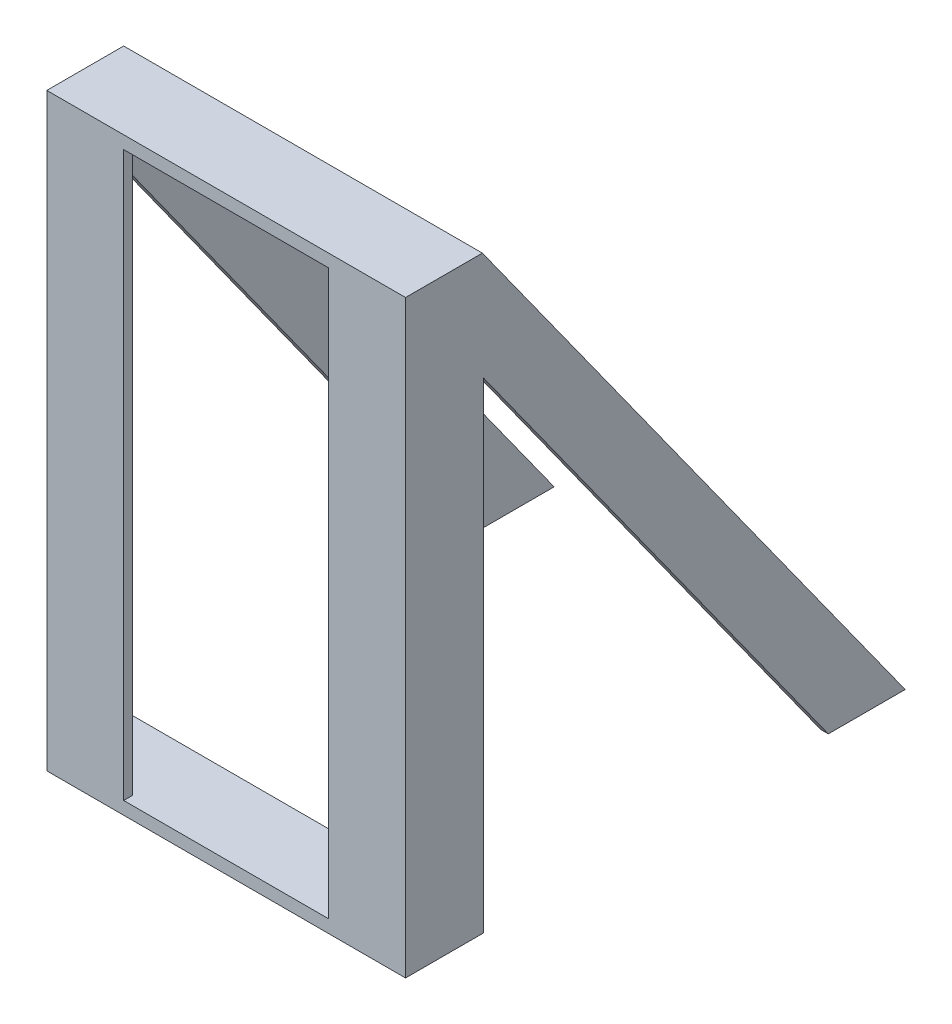
SolidWorks part; units mm, degrees
ref_plane "Front Plane" through (0, 0, 0) normal (0, 0, 1) x (1, 0, 0)
ref_plane "Top Plane" through (0, 0, 0) normal (0, 1, 0) x (1, 0, 0)
ref_plane "Right Plane" through (0, 0, 0) normal (1, 0, 0) x (0, 0, -1)
sketch "Sketch1" plane through (0, 0, 0) normal (0, 1, 0) x (1, 0, 0)
  line L0 (0, 0) -> (0, 30)
  line L1 (0, 0) -> (30, 0)
  line L2 (0, 30) -> (3.4, 30)
  line L3 (30, 0) -> (30, 3.4)
  line L6 (3.4, 30) -> (3.4, 3.4)
  line L7 (3.4, 3.4) -> (30, 3.4)
extrude "Boss-Extrude1" add sketch "Sketch1" along normal blind 225
sketch "Sketch2" plane through (0, 0, 0) normal (0, -1, 0) x (-1, 0, 0)
  line L0 (0, 0) -> (-140, 0)
  line L2 (0, 0) -> (-140, 0)
  line L3 (0, 0) -> (0, 30.4234)
  line L4 (0, 30.4234) -> (-140, 30.4234)
  line L5 (-140, 0) -> (-140, 30.4234)
  line M3 (0, 30) -> (-3.4, 30)
  line M4 (-3.4, 30) -> (-3.4, 3.4)
  line M5 (-3.4, 3.4) -> (-30, 3.4)
  line M6 (-30, 3.4) -> (-30, 0)
extrude "Boss-Extrude2" add sketch "Sketch2" against normal blind 5 contours L5 L0 L3 L4 M6 M5 M4 M3
sketch "Sketch3" plane through (0, 5, 0) normal (0, 1, 0) x (1, 0, 0)
  line L0 (140, 30.4234) -> (136.6, 30.4234)
  line L1 (0, 30.4234) -> (140, 30.4234) construction
  line L2 (140, 0) -> (110, 0)
  line L3 (30, 0) -> (140, 0) construction
  line L4 (110, 0) -> (110, 3.4)
  line L5 (136.6, 30.4234) -> (136.6, 3.4)
  line L6 (136.6, 3.4) -> (110, 3.4)
  line L15 (140, 0) -> (140, 30.4234)
  line L16 (140, 30.4234) -> (0, 30.4234)
  line L17 (0, 30.4234) -> (0, 30)
  line L18 (0, 30) -> (3.4, 30)
  line L19 (3.4, 30) -> (3.4, 3.4)
  line L20 (3.4, 3.4) -> (30, 3.4)
  line L21 (30, 3.4) -> (30, 0)
  line L22 (30, 0) -> (140, 0)
  line L24 (140, 30.4234) -> (0, 30.4234)
  line L25 (0, 30.4234) -> (0, 30)
  line L26 (0, 30) -> (3.4, 30)
  line L27 (3.4, 30) -> (3.4, 3.4)
  line L28 (3.4, 3.4) -> (30, 3.4)
  line L29 (30, 3.4) -> (30, 0)
  line L30 (30, 0) -> (140, 0)
  line M12 (140, 0) -> (140, 30.4234)
  line M13 (140, 30.4234) -> (0, 30.4234)
  line M19 (30, 0) -> (140, 0)
  dimension "D1" = 0
extrude "Boss-Extrude3" add sketch "Sketch3" along normal blind 220 contours L5 L6 L4 M19 M12 M13
sketch "Sketch4" plane through (0, 225, 0) normal (0, 1, 0) x (1, 0, 0)
  line L1 (0, 30) -> (140, 30)
  line L2 (0, 30) -> (0, 0)
  line L3 (0, 0) -> (140, 0)
  line L4 (140, 30) -> (140, 0)
extrude "Boss-Extrude4" add sketch "Sketch4" along normal blind 5
sketch "Sketch5" plane through (140, 0, 0) normal (1, 0, 0) x (0, 0, -1)
  line L0 (0, 0) -> (195, 0)
  line L1 (30, 230) -> (195, 0)
  line L2 (0, 0) -> (0, 30)
  line L3 (0, 30) -> (143.4783, 30)
  line L4 (195, 0) -> (165, 0)
  line L5 (165, 0) -> (0, 230)
  line L6 (0, 230) -> (0, 0) construction
  line M6 (30.4234, 0) -> (30.4234, 225)
  line M7 (30.4234, 225) -> (30, 225)
  line M8 (30, 225) -> (30, 230)
extrude "Boss-Extrude5" add sketch "Sketch5" against normal blind 3 contours L5 L0 L1 M8 M7 M6
sketch "Sketch6" plane through (0, 0, 0) normal (-1, 0, 0) x (0, 0, 1)
  line L0 (-30, 230) -> (-195, 0)
  line L1 (-195, 0) -> (-165, 0)
  line L2 (-165, 0) -> (0, 230)
  line L3 (-30, 230) -> (0, 230)
extrude "Boss-Extrude6" add sketch "Sketch6" against normal blind 3
